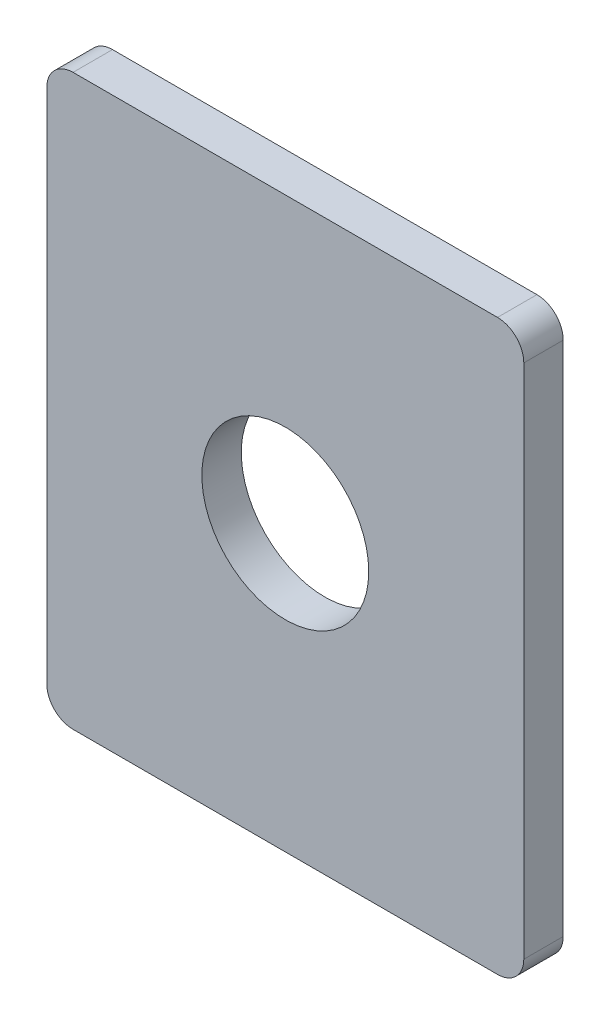
SolidWorks part; units mm, degrees
material "Custom Plastic"
ref_plane "X-Y Datum" through (0, 0, 0) normal (0, 0, 1) x (1, 0, 0)
ref_plane "X-Z Datum" through (0, 0, 0) normal (0, 1, 0) x (1, 0, 0)
ref_plane "Y-Z Datum" through (0, 0, 0) normal (1, 0, 0) x (0, 0, -1)
sketch "Sketch1" plane through (0, 0, 0) normal (0, 0, 1) x (1, 0, 0)
  line L1 (-18.15, 21.65) -> (18.15, 21.65)
  line L2 (-18.15, 21.65) -> (-18.15, -21.65)
  line L3 (-18.15, -21.65) -> (18.15, -21.65)
  line L4 (18.15, 21.65) -> (18.15, -21.65)
  line L5 (-18.15, 21.65) -> (18.15, -21.65) construction
  line L6 (-18.15, -21.65) -> (18.15, 21.65) construction
  circle A0 centre (0, 0) radius 6.35
  point P0 (0, 0)
  dimension "D3" = 12.7
  dimension "D1" = 43.3
  dimension "D2" = 36.3
extrude "Boss-Extrude1" add sketch "Sketch1" along normal blind 3
fillet "Fillet1" radius 2 4 edges at (-18.15, 21.65, 1.5) (-18.15, -21.65, 1.5) (18.15, -21.65, 1.5) (18.15, 21.65, 1.5)
